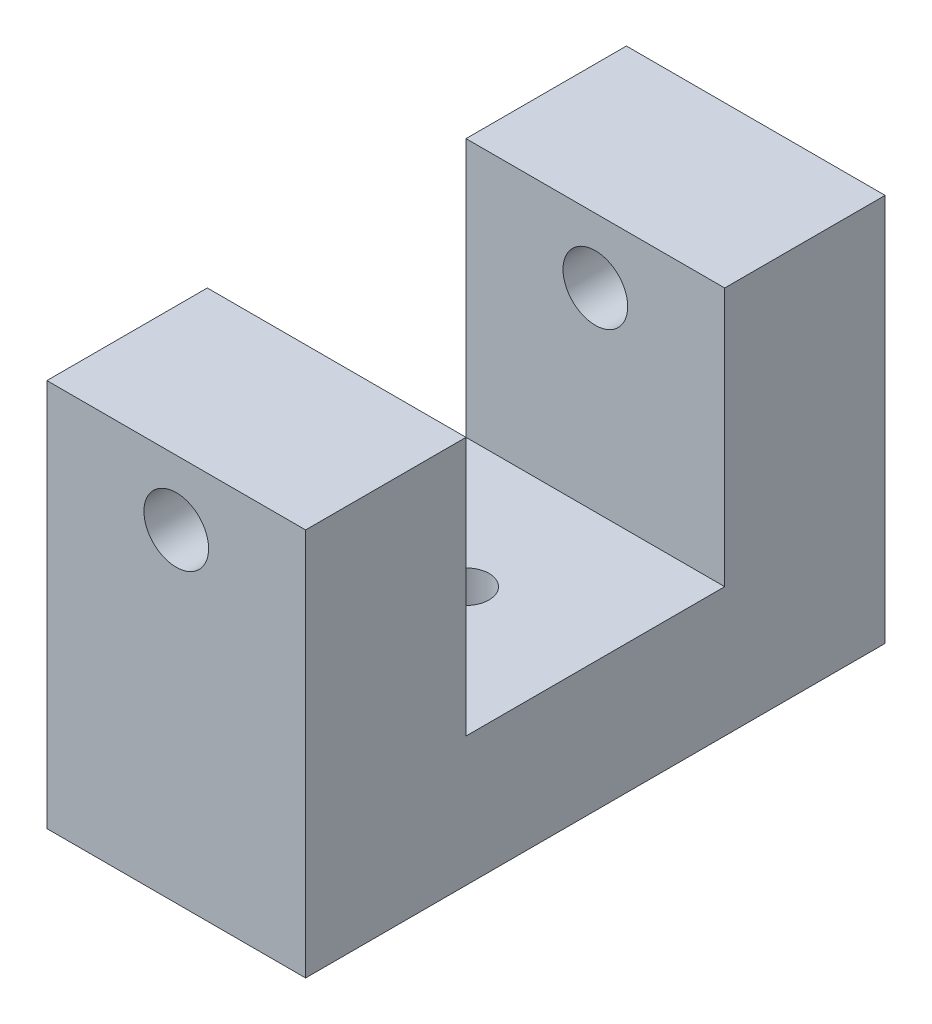
SolidWorks part; units mm, degrees
ref_plane "Front Plane" through (0, 0, 0) normal (0, 0, 1) x (1, 0, 0)
ref_plane "Top Plane" through (0, 0, 0) normal (0, 1, 0) x (1, 0, 0)
ref_plane "Right Plane" through (0, 0, 0) normal (1, 0, 0) x (0, 0, -1)
sketch "Sketch1" plane through (0, 0, 0) normal (0, 1, 0) x (1, 0, 0)
  line L1 (-6.35, -14.224) -> (6.35, -14.224)
  line L2 (-6.35, -14.224) -> (-6.35, 14.224)
  line L3 (-6.35, 14.224) -> (6.35, 14.224)
  line L4 (6.35, -14.224) -> (6.35, 14.224)
  line L5 (-6.35, -14.224) -> (6.35, 14.224) construction
  line L6 (-6.35, 14.224) -> (6.35, -14.224) construction
  point P0 (0, 0)
  dimension "D1" = 12.7
  dimension "D2" = 28.448
extrude "Boss-Extrude1" add sketch "Sketch1" along normal blind 19.05
sketch "Sketch2" plane through (6.35, 0, 0) normal (1, 0, 0) x (0, 0, -1)
  line L0 (0, 19.05) -> (0, 0) construction
  line L1 (-14.224, 19.05) -> (14.224, 19.05) construction
  line L2 (-14.224, 0) -> (14.224, 0) construction
  line L3 (-6.35, 6.35) -> (6.35, 6.35)
  line L4 (-6.35, 6.35) -> (-6.35, 19.05)
  line L5 (-6.35, 19.05) -> (6.35, 19.05)
  line L6 (6.35, 6.35) -> (6.35, 19.05)
  line L7 (-6.35, 6.35) -> (6.35, 19.05) construction
  line L8 (-6.35, 19.05) -> (6.35, 6.35) construction
  point P5 (0, 12.7)
  dimension "D1" = 6.35
  dimension "D2" = 12.7
extrude "Cut-Extrude1" cut sketch "Sketch2" against normal through all
sketch "Sketch5" plane through (0, 0, 14.224) normal (0, 0, 1) x (1, 0, 0)
  line L0 (0, 19.05) -> (0, 0) construction
  line L1 (-6.35, 19.05) -> (6.35, 19.05) construction
  line L2 (-6.35, 0) -> (6.35, 0) construction
  circle A0 centre (0, 15.875) radius 1.5875
  dimension "D1" = 3.175
  dimension "D2" = 3.175
extrude "Cut-Extrude2" cut sketch "Sketch5" against normal through all
hole_wizard "#4-40 Tapped Hole1" positions "Sketch7" profile "Sketch8" tap size "#4-40" standard "Progressive" end condition up to next
sketch "Sketch7" plane through (0, 0, 0) normal (0, -1, 0) x (-1, 0, 0)
  point P0 (0, 0)
sketch "Sketch8" plane through (0, 0, 0) normal (1, 0, 0) x (0, 0, -1)
  line L0 (0, 0) -> (0, 6.35)
  line L1 (0, 6.35) -> (1.1303, 6.35)
  line L2 (1.1303, 6.35) -> (1.1303, 0)
  line L5 (1.1303, 0) -> (0, 0)
  line L11 (0, -6.35) -> (0, 107.95) construction
  dimension "Thru Tap Drill Dia." = 2.2606
  dimension "Thru Tap Drill Depth" = 6.35
cosmetic thread "Hole Thread1" parameters "D2"=2.8448
